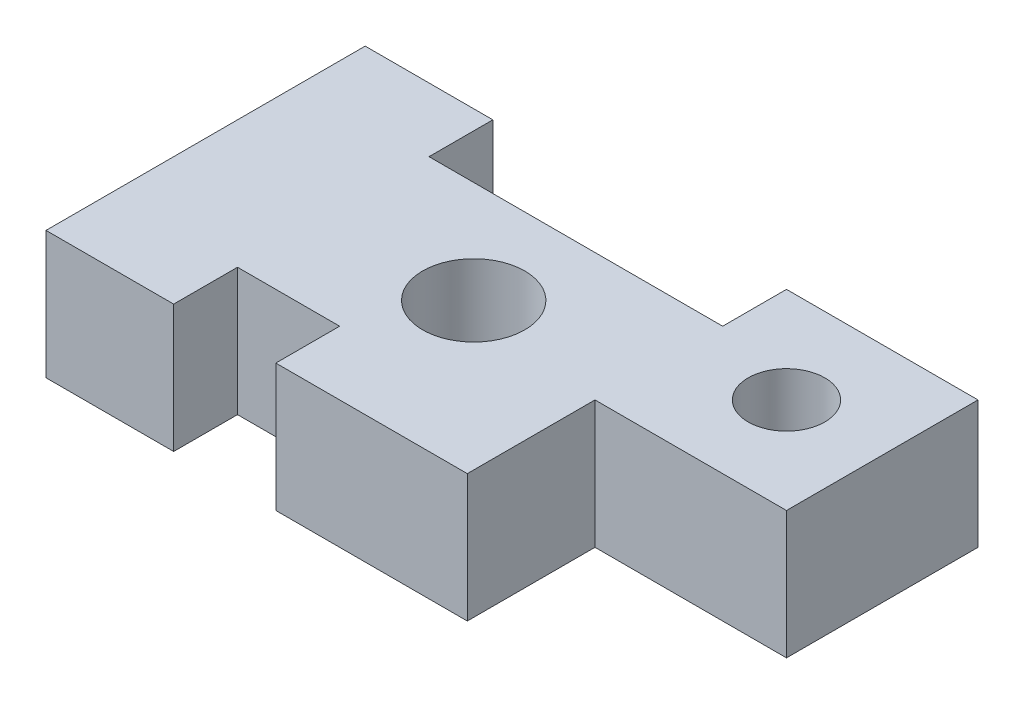
SolidWorks part; units mm, degrees
ref_plane "Front Plane" through (0, 0, 0) normal (0, 0, 1) x (1, 0, 0)
ref_plane "Top Plane" through (0, 0, 0) normal (0, 1, 0) x (1, 0, 0)
ref_plane "Right Plane" through (0, 0, 0) normal (1, 0, 0) x (0, 0, -1)
sketch "Sketch1" plane through (0, 0, 0) normal (0, 1, 0) x (1, 0, 0)
  line L0 (0, 0) -> (100, 0)
  line L1 (0, 0) -> (0, 250)
  line L2 (100, 0) -> (100, 50)
  line L3 (100, 50) -> (180, 50)
  line L4 (180, 50) -> (180, 0)
  line L5 (180, 0) -> (330, 0)
  line L6 (330, 0) -> (330, 100)
  line L7 (330, 100) -> (480, 100)
  line L8 (480, 100) -> (480, 250)
  line L9 (480, 250) -> (330, 250)
  line L10 (330, 250) -> (330, 200)
  line L11 (330, 200) -> (100, 200)
  line L12 (100, 200) -> (100, 250)
  line L13 (100, 250) -> (0, 250)
  circle A0 centre (215, 120) radius 40
  circle A1 centre (405, 175) radius 30
  dimension "D9" = 80
  dimension "D12" = 60
  dimension "D1" = 250
  dimension "D2" = 100
  dimension "D3" = 50
  dimension "D4" = 80
  dimension "D5" = 150
  dimension "D6" = 100
  dimension "D7" = 150
  dimension "D8" = 230
  dimension "D10" = 115
  dimension "D11" = 80
  dimension "D13" = 75
  dimension "D14" = 75
  dimension "D15" = 50
extrude "Boss-Extrude1" add sketch "Sketch1" along normal blind 100
